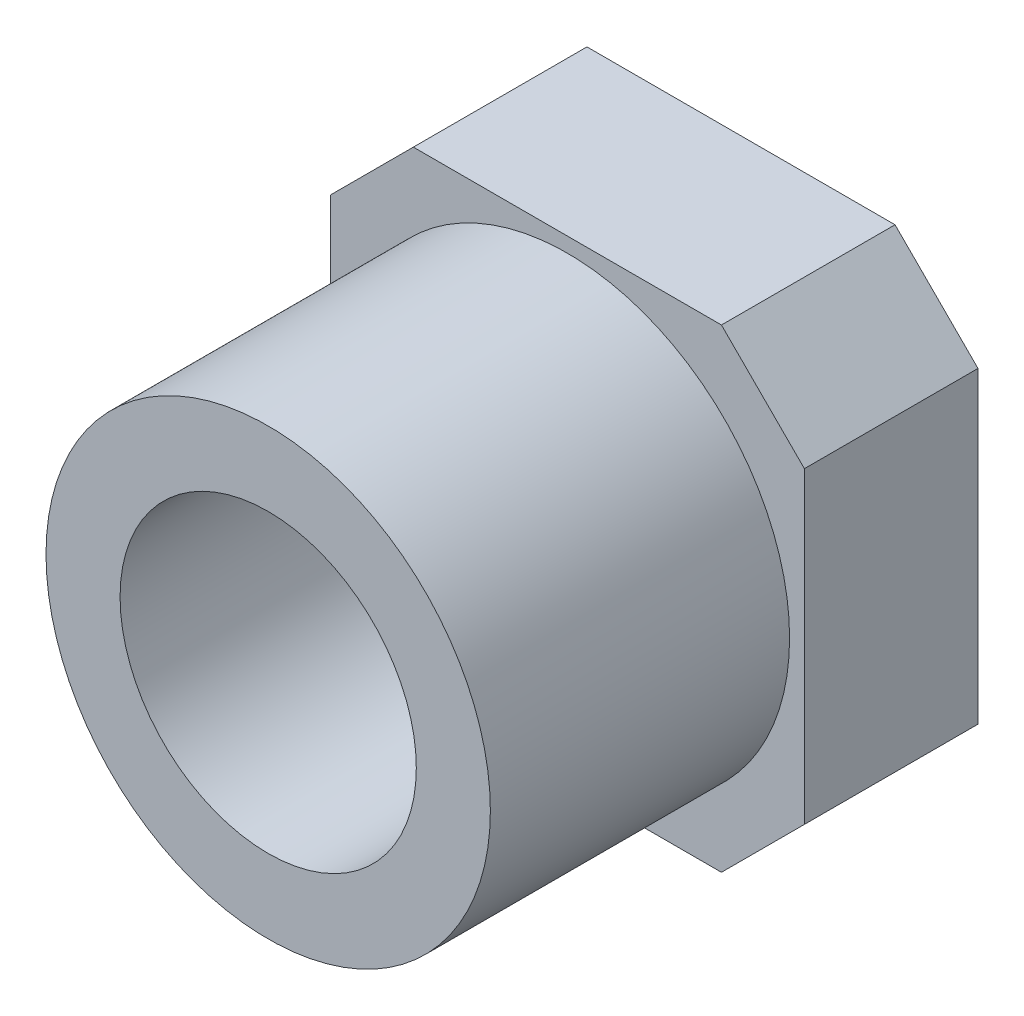
SolidWorks part; units mm, degrees
material "6061-T6 (SS)"
ref_plane "Front Plane" through (0, 0, 0) normal (0, 0, 1) x (1, 0, 0)
ref_plane "Top Plane" through (0, 0, 0) normal (0, 1, 0) x (1, 0, 0)
ref_plane "Right Plane" through (0, 0, 0) normal (1, 0, 0) x (0, 0, -1)
sketch "Sketch1" plane through (0, 0, 0) normal (0, 0, 1) x (1, 0, 0)
  circle A0 centre (0, 0) radius 6.35
  circle A1 centre (0, 0) radius 9.525
  dimension "D1" = 19.05
  dimension "D2" = 12.7
extrude "Boss-Extrude1" add sketch "Sketch1" along normal blind 12.827
sketch "Sketch2" plane through (0, 0, 0) normal (0, 0, -1) x (-1, 0, 0)
  line L1 (-10.16, -10.16) -> (10.16, -10.16)
  line L2 (-10.16, -10.16) -> (-10.16, 10.16)
  line L3 (-10.16, 10.16) -> (10.16, 10.16)
  line L4 (10.16, -10.16) -> (10.16, 10.16)
  line L5 (-10.16, -10.16) -> (10.16, 10.16) construction
  line L6 (-10.16, 10.16) -> (10.16, -10.16) construction
  circle A0 centre (0, 0) radius 6.35
  dimension "D1" = 20.32
extrude "Boss-Extrude2" add sketch "Sketch2" along normal blind 7.4422
chamfer "Chamfer1" distance 3.556 angle 45 4 edges at (10.16, -10.16, -3.7211) (-10.16, -10.16, -3.7211) (-10.16, 10.16, -3.7211) (10.16, 10.16, -3.7211)
